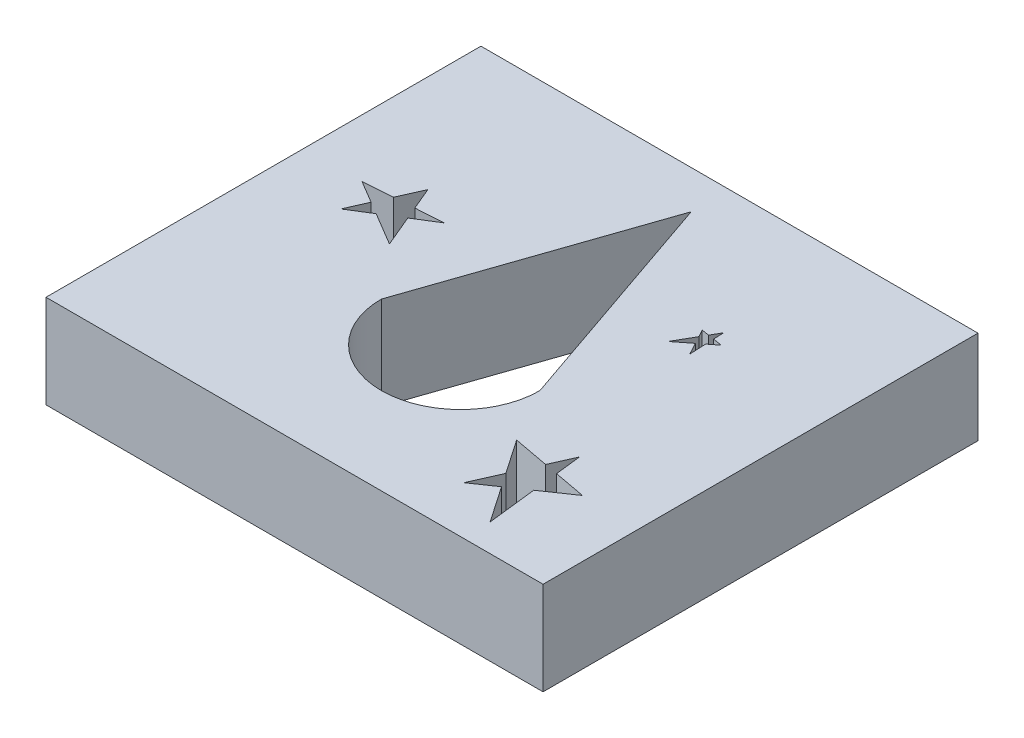
SolidWorks part; units mm, degrees
ref_plane "Front Plane" through (0, 0, 0) normal (0, 0, 1) x (1, 0, 0)
ref_plane "Top Plane" through (0, 0, 0) normal (0, 1, 0) x (1, 0, 0)
ref_plane "Right Plane" through (0, 0, 0) normal (1, 0, 0) x (0, 0, -1)
sketch "Sketch1" plane through (0, 0, 0) normal (0, 1, 0) x (1, 0, 0)
  line L0 (-34.8025, 21.0859) -> (-37.3543, 13.665)
  line L1 (-42.8025, 22.3185) -> (-26.8025, 22.3185)
  line L2 (-42.8025, 22.3185) -> (-42.8025, 8.3185)
  line L3 (-42.8025, 8.3185) -> (-26.8025, 8.3185)
  line L4 (-26.8025, 22.3185) -> (-26.8025, 8.3185)
  line L5 (-32.2508, 13.665) -> (-34.8025, 21.0859)
  line L6 (-39.6587, 17.4666) -> (-39.9992, 16.698)
  line L7 (-40.5179, 15.5268) -> (-39.8179, 15.961)
  line L8 (-38.4609, 16.8027) -> (-39.3538, 16.7419)
  line L9 (-40.9476, 16.6334) -> (-40.2197, 16.2001)
  line L10 (-38.7604, 15.3315) -> (-39.1893, 16.3509)
  line L11 (-29.7641, 12.4543) -> (-30.0989, 11.6986)
  line L12 (-30.9066, 9.8751) -> (-30.1886, 10.3672)
  line L13 (-28.6426, 11.4268) -> (-29.6682, 11.6182)
  line L14 (-31.2481, 11.9132) -> (-30.4923, 10.8104)
  line L15 (-29.3912, 9.2038) -> (-29.5731, 10.789)
  line L16 (-39.9992, 16.698) -> (-40.9476, 16.6334)
  line L17 (-40.2197, 16.2001) -> (-40.5179, 15.5268)
  line L18 (-39.1893, 16.3509) -> (-38.4609, 16.8027)
  line L19 (-39.8179, 15.961) -> (-38.7604, 15.3315)
  line L20 (-39.3538, 16.7419) -> (-39.6587, 17.4666)
  line L21 (-30.1886, 10.3672) -> (-29.3912, 9.2038)
  line L22 (-30.4923, 10.8104) -> (-30.9066, 9.8751)
  line L23 (-29.5731, 10.789) -> (-28.6426, 11.4268)
  line L24 (-29.6682, 11.6182) -> (-29.7641, 12.4543)
  line L25 (-30.0989, 11.6986) -> (-31.2481, 11.9132)
  line L26 (-30.9066, 18.2348) -> (-31.083, 17.9271)
  line L27 (-31.559, 17.0971) -> (-31.0662, 17.4833)
  line L28 (-30.5974, 17.8507) -> (-30.8921, 17.8971)
  line L29 (-31.3264, 17.9654) -> (-31.1978, 17.727)
  line L30 (-30.8577, 17.0971) -> (-30.8806, 17.6288)
  line L31 (-30.8806, 17.6288) -> (-30.5974, 17.8507)
  line L32 (-31.0662, 17.4833) -> (-30.8577, 17.0971)
  line L33 (-31.1978, 17.727) -> (-31.559, 17.0971)
  line L34 (-31.083, 17.9271) -> (-31.3264, 17.9654)
  line L35 (-30.8921, 17.8971) -> (-30.9066, 18.2348)
  arc A0 (-37.3543, 13.665) -> (-32.2508, 13.665) centre (-34.8025, 13.665) ccw
  point P38 (-31.559, 17.0971)
  point P39 (-30.8806, 17.0971)
  dimension "D1" = 16
  dimension "D2" = 14
extrude "Boss-Extrude1" add sketch "Sketch1" along normal blind 3
